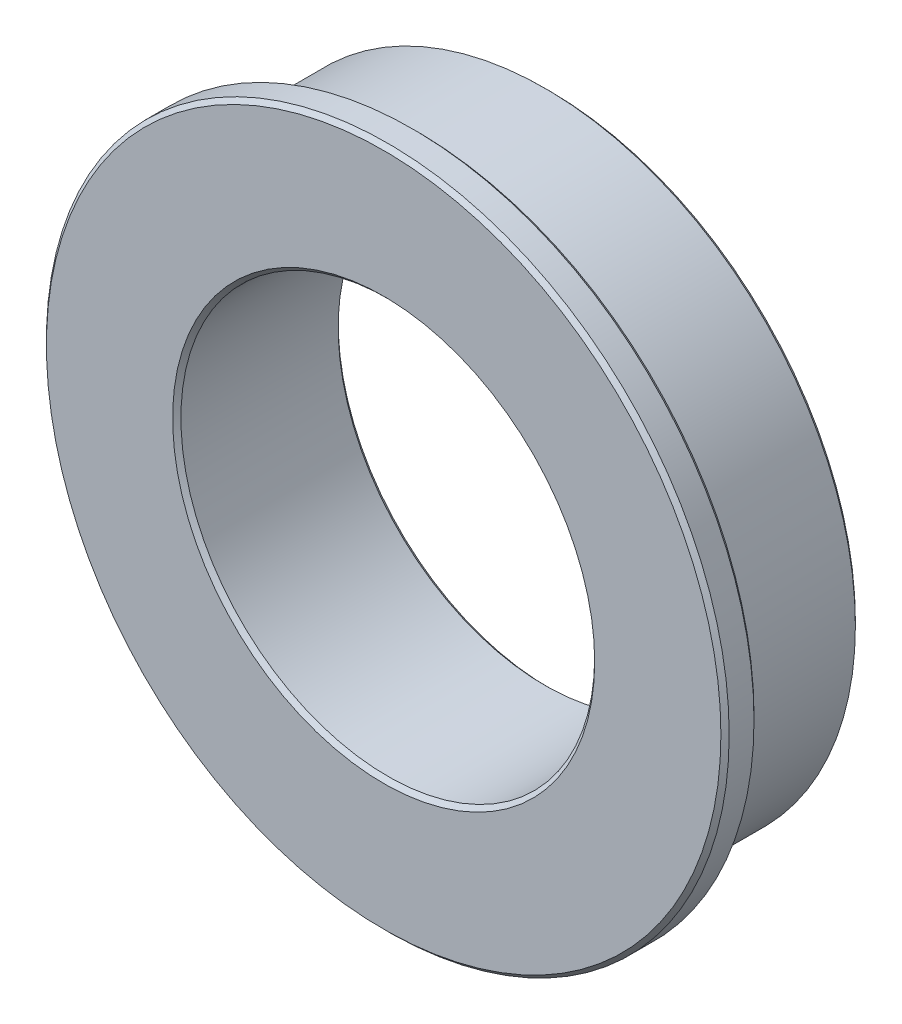
SolidWorks part; units mm, degrees
material "1023 碳钢板 (SS)"
ref_plane "前视基准面" through (0, 0, 0) normal (0, 0, 1) x (1, 0, 0)
ref_plane "上视基准面" through (0, 0, 0) normal (0, 1, 0) x (1, 0, 0)
ref_plane "右视基准面" through (0, 0, 0) normal (1, 0, 0) x (0, 0, -1)
other "Configuration Table"
sketch "草图1" plane through (0, 0, 0) normal (0, 0, 1) x (1, 0, 0)
  circle A0 centre (0, 0) radius 7.5
  circle A1 centre (0, 0) radius 5
  dimension "D1" = 10
  dimension "D2" = 15
extrude "凸台-拉伸1" add sketch "草图1" along normal blind 4
sketch "草图2" plane through (0, 0, 4) normal (0, 0, 1) x (1, 0, 0)
  circle A0 centre (0, 0) radius 8.25
  circle A1 centre (0, 0) radius 7.5 construction
  circle A2 centre (0, 0) radius 7.5
  dimension "D1" = 16.5
extrude "凸台-拉伸2" add sketch "草图2" against normal blind 0.8
chamfer "倒角1" distance 0.1 angle 45 5 edges at (5, 0, 4) (5, 0, 0) (7.5, 0, 0) (8.25, 0, 3.2) (8.25, 0, 4)
